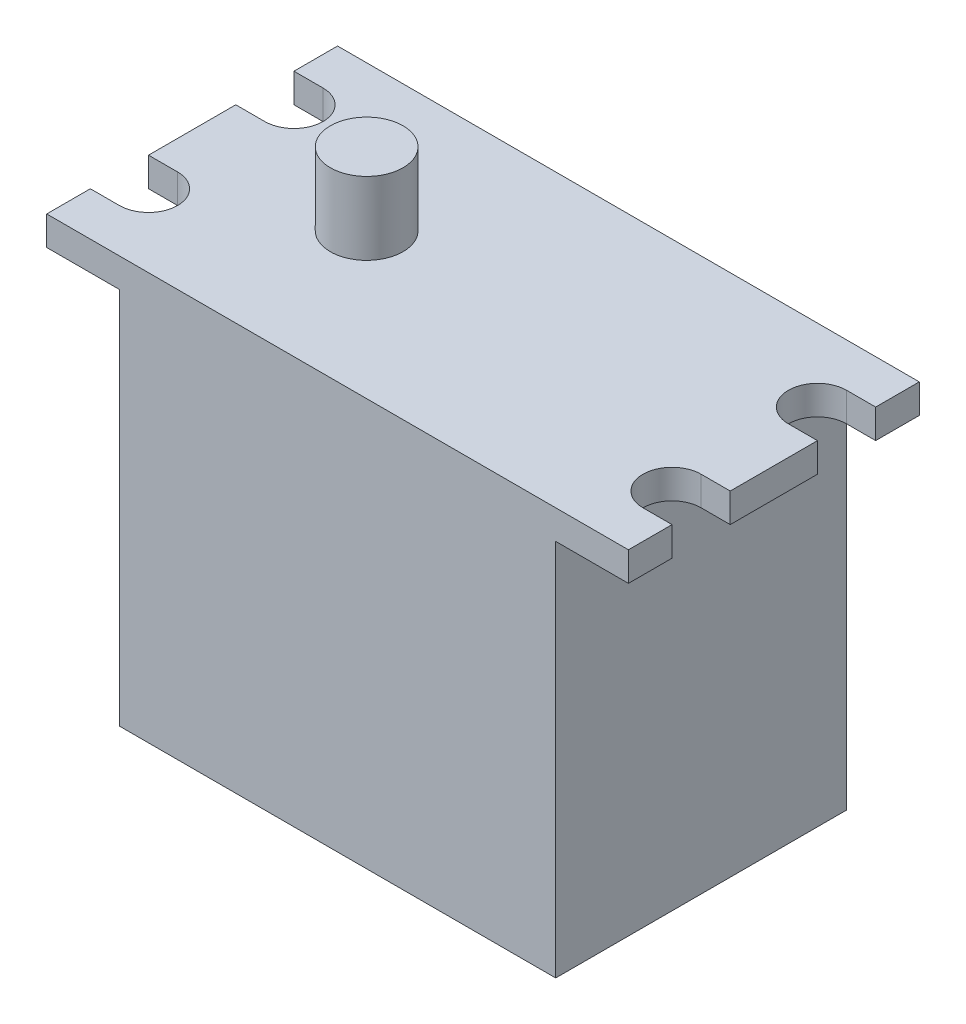
SolidWorks part; units mm, degrees
ref_plane "Front Plane" through (0, 0, 0) normal (0, 0, 1) x (1, 0, 0)
ref_plane "Top Plane" through (0, 0, 0) normal (0, 1, 0) x (1, 0, 0)
ref_plane "Right Plane" through (0, 0, 0) normal (1, 0, 0) x (0, 0, -1)
sketch "Sketch1" plane through (0, 0, 0) normal (0, 1, 0) x (1, 0, 0)
  line L1 (-12.7, -6.35) -> (12.7, -6.35)
  line L2 (-12.7, -6.35) -> (-12.7, 6.35)
  line L3 (-12.7, 6.35) -> (12.7, 6.35)
  line L4 (12.7, -6.35) -> (12.7, 6.35)
  line L5 (-12.7, -6.35) -> (12.7, 6.35) construction
  line L6 (-12.7, 6.35) -> (12.7, -6.35) construction
  point P0 (0, 0)
  dimension "D1" = 12.7
  dimension "D2" = 25.4
extrude "Boss-Extrude1" add sketch "Sketch1" along normal blind 17.78
sketch "Sketch2" plane through (0, 0, 0) normal (0, -1, 0) x (1, 0, 0)
  line L0 (-12.7, 6.35) -> (12.7, 6.35) construction
  line L1 (-12.7, -6.35) -> (-9.525, -6.35)
  line L2 (-12.7, -6.35) -> (-12.7, 6.35)
  line L3 (-12.7, 6.35) -> (-9.525, 6.35)
  line L4 (-9.525, -6.35) -> (-9.525, 6.35)
  line L6 (12.7, -6.35) -> (9.525, -6.35)
  line L7 (12.7, -6.35) -> (12.7, 6.35)
  line L8 (12.7, 6.35) -> (9.525, 6.35)
  line L9 (9.525, -6.35) -> (9.525, 6.35)
  dimension "D1" = 3.175
  dimension "D2" = 3.175
extrude "Cut-Extrude1" cut sketch "Sketch2" against normal blind 16.51
sketch "Sketch3" plane through (0, 17.78, 0) normal (0, 1, 0) x (1, 0, 0)
  line L0 (-12.7, 6.35) -> (-12.7, -6.35) construction
  circle A0 centre (-5.08, 0) radius 1.5875
  point P4 (-12.7, 0)
  dimension "D1" = 3.175
  dimension "D2" = 7.62
extrude "Boss-Extrude2" add sketch "Sketch3" along normal blind 3.175
sketch "Sketch4" plane through (0, 17.78, 0) normal (0, 1, 0) x (1, 0, 0)
  line L0 (-11.43, -6.35) -> (-11.43, 6.35) construction
  line L1 (-12.7, -6.35) -> (12.7, -6.35) construction
  line L2 (12.7, 6.35) -> (-12.7, 6.35) construction
  line L3 (0, 0) -> (0, 3.5712) construction
  line L4 (-12.7, 6.35) -> (-12.7, -6.35) construction
  line L5 (-11.43, -4.445) -> (-12.7, -4.445)
  line L6 (-12.7, -4.445) -> (-12.7, -1.905)
  line L7 (-12.7, -1.905) -> (-11.43, -1.905)
  line L8 (-11.43, 1.905) -> (-12.7, 1.905)
  line L9 (-12.7, 1.905) -> (-12.7, 4.445)
  line L10 (-12.7, 4.445) -> (-11.43, 4.445)
  line L11 (11.43, -6.35) -> (11.43, 6.35) construction
  line L12 (12.7, 4.445) -> (11.43, 4.445)
  line L13 (12.7, 1.905) -> (12.7, 4.445)
  line L14 (11.43, 1.905) -> (12.7, 1.905)
  line L15 (12.7, -1.905) -> (11.43, -1.905)
  line L16 (12.7, -4.445) -> (12.7, -1.905)
  line L17 (11.43, -4.445) -> (12.7, -4.445)
  arc A0 (-11.43, -4.445) -> (-11.43, -1.905) centre (-11.43, -3.175) ccw
  arc A1 (-11.43, 1.905) -> (-11.43, 4.445) centre (-11.43, 3.175) ccw
  arc A2 (11.43, 1.905) -> (11.43, 4.445) centre (11.43, 3.175) cw
  arc A3 (11.43, -4.445) -> (11.43, -1.905) centre (11.43, -3.175) cw
  dimension "D2" = 3.175
  dimension "D3" = 3.175
  dimension "D1" = 1.27
extrude "Cut-Extrude2" cut sketch "Sketch4" against normal through all
